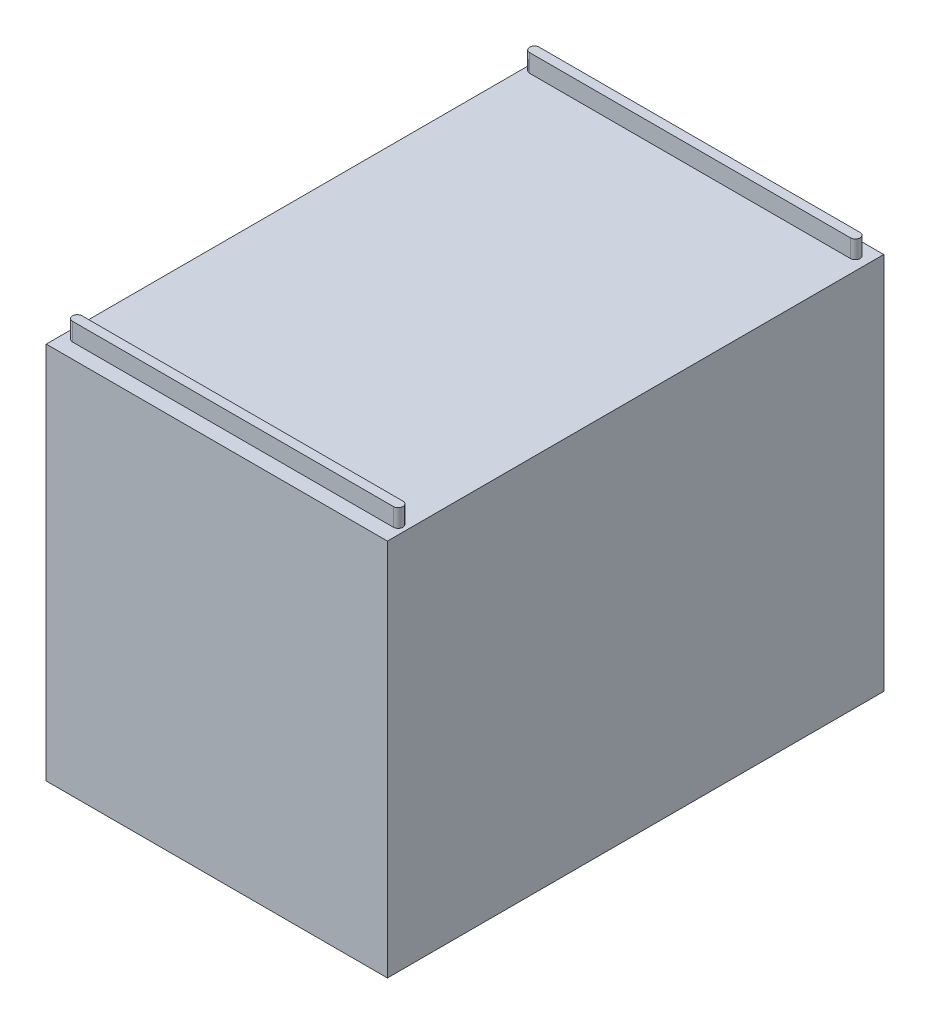
SolidWorks part; units mm, degrees
ref_plane "Front Plane" through (0, 0, 0) normal (0, 0, 1) x (1, 0, 0)
ref_plane "Top Plane" through (0, 0, 0) normal (0, 1, 0) x (1, 0, 0)
ref_plane "Right Plane" through (0, 0, 0) normal (1, 0, 0) x (0, 0, -1)
sketch "Sketch1" plane through (0, 0, 0) normal (1, 0, 0) x (0, 0, -1)
  line L1 (-109.1133, 51.4956) -> (-26.1853, 51.4956)
  line L2 (-109.1133, 51.4956) -> (-109.1133, -11.7253)
  line L3 (-109.1133, -11.7253) -> (-26.1853, -11.7253)
  line L4 (-26.1853, 51.4956) -> (-26.1853, -11.7253)
extrude "Boss-Extrude1" add sketch "Sketch1" along normal blind 2
sketch "Sketch2" plane through (2, 0, 0) normal (1, 0, 0) x (0, 0, -1)
  line L0 (-26.1853, -11.7253) -> (-26.1853, 51.4956) construction
  line L1 (-109.1133, 51.4956) -> (-26.1853, 51.4956)
  line L2 (-109.1133, 51.4956) -> (-109.1133, 48.0298)
  line L3 (-109.1133, 48.0298) -> (-26.1853, 48.0298)
  line L4 (-26.1853, 51.4956) -> (-26.1853, 48.0298)
extrude "Boss-Extrude2" add sketch "Sketch2" along normal blind 55
sketch "Sketch3" plane through (2, 0, 0) normal (1, 0, 0) x (0, 0, -1)
  line L0 (-26.1853, -11.7253) -> (-26.1853, 48.0298) construction
  line L1 (-109.1133, -11.7253) -> (-26.1853, -11.7253)
  line L2 (-109.1133, -11.7253) -> (-109.1133, -7.758)
  line L3 (-109.1133, -7.758) -> (-26.1853, -7.758)
  line L4 (-26.1853, -11.7253) -> (-26.1853, -7.758)
extrude "Boss-Extrude3" add sketch "Sketch3" along normal blind 55
sketch "Sketch4" plane through (2, 0, 0) normal (1, 0, 0) x (0, 0, -1)
  line L0 (-26.1853, -7.758) -> (-109.1133, -7.758) construction
  line L1 (-109.1133, 48.0298) -> (-104.8914, 48.0298)
  line L2 (-109.1133, 48.0298) -> (-109.1133, -7.758)
  line L3 (-109.1133, -7.758) -> (-104.8914, -7.758)
  line L4 (-104.8914, 48.0298) -> (-104.8914, -7.758)
extrude "Boss-Extrude4" add sketch "Sketch4" along normal blind 55
sketch "Sketch5" plane through (0, 48.0298, 0) normal (0, -1, 0) x (-1, 0, 0)
  line L1 (-2, -104.8914) -> (-2, -26.1853) construction
  line L2 (-57, -26.1853) -> (-2, -26.1853)
  line L3 (-57, -26.1853) -> (-57, -30.1211)
  line L4 (-57, -30.1211) -> (-2, -30.1211)
  line L5 (-2, -26.1853) -> (-2, -30.1211)
extrude "Boss-Extrude5" add sketch "Sketch5" along normal blind 59
sketch "Sketch6" plane through (0, 0, 0) normal (-1, 0, 0) x (0, 0, 1)
  line L1 (98.159, -0.5593) -> (56.6586, -0.5593)
  line L2 (98.159, -0.5593) -> (98.159, 30.0428)
  line L3 (98.159, 30.0428) -> (56.6586, 30.0428)
  line L4 (56.6586, -0.5593) -> (56.6586, 30.0428)
extrude "Cut-Extrude1" cut sketch "Sketch6" against normal blind 59
sketch "Sketch7" plane through (0, 48.0298, -1.2346) normal (0, -1, 0) x (-1, 0, 0)
  line L1 (-7.0976, -38.0511) -> (-51.6743, -38.0511)
  line L2 (-7.0976, -38.0511) -> (-7.0976, -104.748)
  line L3 (-7.0976, -104.748) -> (-51.6743, -104.748)
  line L4 (-51.6743, -38.0511) -> (-51.6743, -104.748)
extrude "Boss-Extrude6" add sketch "Sketch7" along normal blind 1.0035
sketch "Sketch8" plane through (2, 0, -3.3652) normal (1, 0, 0) x (0, 0, -1)
  line L1 (-40.2127, 0) -> (-50.6787, 0)
  line L2 (-40.2127, 0) -> (-40.2127, 14.1759)
  line L3 (-40.2127, 14.1759) -> (-50.6787, 14.1759)
  line L4 (-50.6787, 0) -> (-50.6787, 14.1759)
extrude "Boss-Extrude7" add sketch "Sketch8" along normal blind 2.5615
sketch "Sketch9" plane through (0, 51.4956, 0) normal (0, 1, 0) x (1, 0, 0)
  line L0 (1.8879, -105.8229) -> (55.5032, -105.8229) construction
  line L1 (1.8879, -105.0301) -> (55.5032, -105.0301)
  line L2 (1.8879, -106.6156) -> (55.5032, -106.6156)
  line L3 (1.2064, -28.7594) -> (54.8217, -28.7594) construction
  line L4 (1.2064, -27.9666) -> (54.8217, -27.9666)
  line L5 (1.2064, -29.5521) -> (54.8217, -29.5521)
  arc A0 (1.8879, -105.0301) -> (1.8879, -106.6156) centre (1.8879, -105.8229) ccw
  arc A1 (55.5032, -106.6156) -> (55.5032, -105.0301) centre (55.5032, -105.8229) ccw
  arc A2 (1.2064, -27.9666) -> (1.2064, -29.5521) centre (1.2064, -28.7594) ccw
  arc A3 (54.8217, -29.5521) -> (54.8217, -27.9666) centre (54.8217, -28.7594) ccw
  point P2 (28.6956, -105.8229)
  point P9 (28.014, -28.7594)
extrude "Boss-Extrude8" add sketch "Sketch9" along normal blind 3
ref_plane "Plane1" through (57, -11.7253, 26.1853) normal (0, 1, 0) x (1, 0, 0)
ref_plane "Plane2" through (57, 51.4956, 109.1133) normal (0, -1, 0) x (-1, 0, 0)
sketch "Sketch13" plane through (57, 0, 0) normal (1, 0, 0) x (0, 0, -1)
  line L1 (-26.1853, 51.4956) -> (-109.1133, 51.4956)
  line L2 (-26.1853, 51.4956) -> (-26.1853, -11.7253)
  line L3 (-26.1853, -11.7253) -> (-109.1133, -11.7253)
  line L4 (-109.1133, 51.4956) -> (-109.1133, -11.7253)
extrude "Boss-Extrude9" add sketch "Sketch13" against normal blind 1
